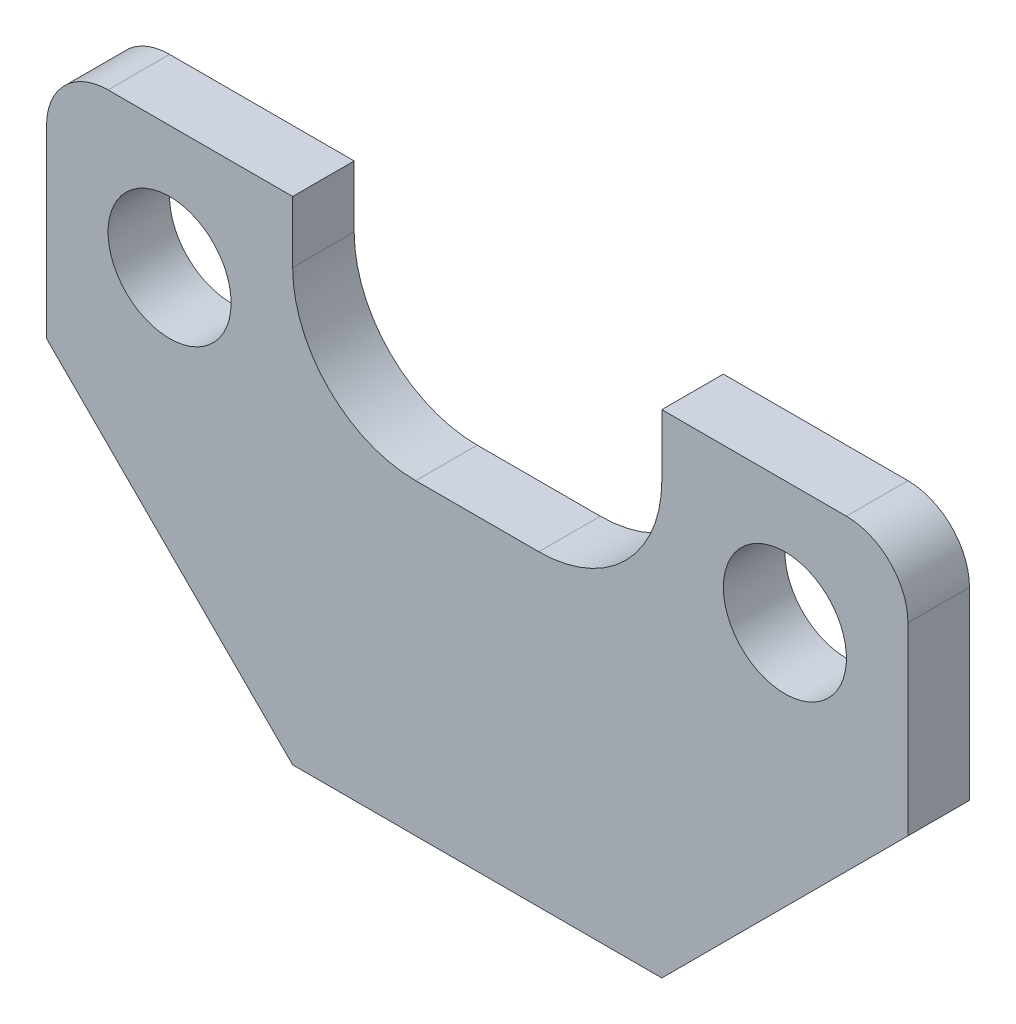
SolidWorks part; units mm, degrees
ref_plane "Front Plane" through (0, 0, 0) normal (0, 0, 1) x (1, 0, 0)
ref_plane "Top Plane" through (0, 0, 0) normal (0, 1, 0) x (1, 0, 0)
ref_plane "Right Plane" through (0, 0, 0) normal (1, 0, 0) x (0, 0, -1)
sketch "Sketch1" plane through (0, 0, 0) normal (0, 0, 1) x (1, 0, 0)
  line L0 (0, 0) -> (0, 50000) construction
  line L1 (15, 0) -> (-15, 0)
  line L2 (-15, 0) -> (-35, 20)
  line L3 (-35, 20) -> (-35, 35)
  line L4 (-30, 40) -> (-15, 40)
  line L5 (-15, 40) -> (-15, 35)
  line L6 (-5, 25) -> (5, 25)
  line L7 (15, 40) -> (15, 35)
  line L8 (30, 40) -> (15, 40)
  line L9 (35, 20) -> (35, 35)
  line L10 (15, 0) -> (35, 20)
  circle A0 centre (-25, 30) radius 5
  arc A1 (-15, 35) -> (-5, 25) centre (-5, 35) ccw
  arc A2 (-30, 40) -> (-35, 35) centre (-30, 35) ccw
  arc A3 (30, 40) -> (35, 35) centre (30, 35) cw
  arc A4 (15, 35) -> (5, 25) centre (5, 35) cw
  circle A5 centre (25, 30) radius 5
  point P17 (0, 25)
  point P18 (0, 0)
  dimension "D6" = 10
  dimension "D5" = 10
  dimension "D9" = 5
  dimension "D10" = 15
  dimension "D1" = 15
  dimension "D2" = 20
  dimension "D3" = 20
  dimension "D4" = 40
  dimension "D7" = 10
  dimension "D8" = 30
  dimension "D11" = 15
extrude "Boss-Extrude1" add sketch "Sketch1" along normal blind 5
